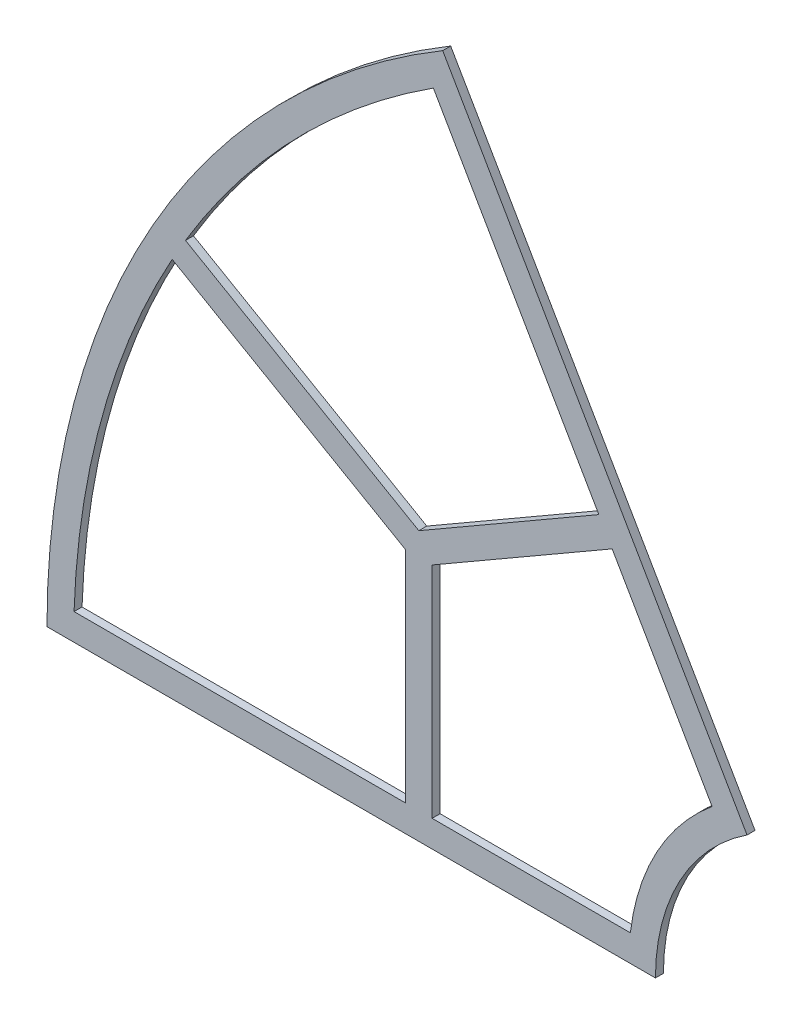
SolidWorks part; units mm, degrees
ref_plane "Front Plane" through (0, 0, 0) normal (0, 0, 1) x (1, 0, 0)
ref_plane "Top Plane" through (0, 0, 0) normal (0, 1, 0) x (1, 0, 0)
ref_plane "Right Plane" through (0, 0, 0) normal (1, 0, 0) x (0, 0, -1)
sketch "Sketch1" plane through (0, 0, 0) normal (0, 0, 1) x (1, 0, 0)
  line L0 (0, 0) -> (-10, 0)
  line L2 (-10, 0) -> (-15, 8.6603)
  line L4 (-340.2, 20) -> (-589.2607, 20)
  line L5 (-194.9205, 280.2917) -> (-319.272, 495.6748)
  line L6 (0, 0) -> (-15, 8.6603)
  line L7 (-109.821, 132.8951) -> (-184.9205, 262.9712)
  line L8 (-83.5769, 127.4389) -> (-312.2692, 523.5457)
  line L9 (-152.4, 0) -> (-609.6, 0)
  line L10 (-171.236, 20) -> (-589.2607, 20) construction
  line L11 (-171.236, 20) -> (-320.2, 20)
  line L13 (-320.2, 20) -> (-320.2, 173.3206)
  line L14 (-310.2, 190.6411) -> (-184.9205, 262.9712)
  line L16 (-340.2, 20) -> (-340.2, 184.8676)
  line L17 (-330.2, 202.1881) -> (-194.9205, 280.2917)
  line L18 (-532.858, 296.0987) -> (-532.9291, 296.1397)
  line L19 (-522.858, 313.4192) -> (-522.9291, 313.4603)
  line L20 (-320.2, 173.3206) -> (-320.2, 184.8676)
  line L21 (-109.821, 132.8951) -> (-319.272, 495.6748) construction
  line L22 (-330.2, 202.1881) -> (-505.5351, 303.4178)
  line L23 (-320.2, 184.8676) -> (-310.2, 190.6411)
  line L24 (-340.2, 184.8676) -> (-515.5351, 286.0973)
  arc A0 (-609.6, 0) -> (-312.2692, 523.5457) centre (0, 0) cw
  arc A1 (-83.5769, 127.4389) -> (-152.4, 0) centre (0, 0) ccw
  arc A2 (-589.2607, 20) -> (-515.5351, 286.0973) centre (0, 0) cw
  arc A3 (-109.821, 132.8951) -> (-144.0514, 94.7151) centre (0, 0) ccw
  arc A4 (-505.5351, 303.4178) -> (-319.272, 495.6748) centre (0, 0) cw
  arc A5 (-154.0514, 77.3946) -> (-171.236, 20) centre (0, 0) ccw
  arc A6 (-589.2607, 20) -> (-319.272, 495.6748) centre (0, 0) cw construction
  arc A7 (-154.0514, 77.3946) -> (-144.0514, 94.7151) centre (0, 0) cw
  arc A8 (-109.821, 132.8951) -> (-171.236, 20) centre (0, 0) ccw construction
  point P3 (-172.6, 281.6315)
  point P6 (0, 0)
  point P7 (-330.2, 0)
  point P10 (-165.1, 285.9616)
  point P11 (-527.9291, 304.8)
  point P12 (-330.2, 0)
  point P13 (-330.2, 190.6411)
  point P16 (-131.9823, 76.2)
  point P22 (-126.9823, 84.8603)
  point P24 (-320.2, 0)
  point P25 (-320.2, 184.8676)
  point P26 (-167.6, 272.9712)
  point P27 (-136.9823, 67.5397)
  point P29 (-340.2, 0)
  point P30 (-340.2, 196.4146)
  point P31 (-177.6, 290.2917)
  dimension "D4" = 330.2
  dimension "D3" = 330.2
  dimension "D1" = 20
extrude "Boss-Extrude1" add sketch "Sketch1" along normal blind 6 contours A1 L8 A0 L9 A7 A5 L11 L13 L20 L23 L14 L7 A3 L4 A2 L24 L16 L22 A4 L5 L17
